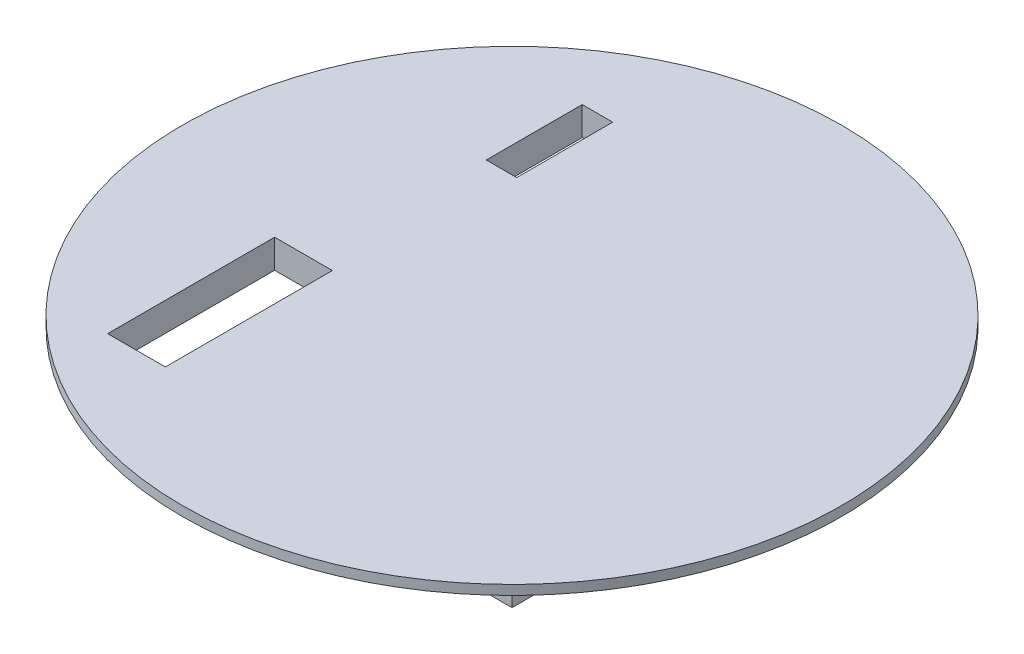
SolidWorks part; units mm, degrees
ref_plane "Front Plane" through (0, 0, 0) normal (0, 0, 1) x (1, 0, 0)
ref_plane "Top Plane" through (0, 0, 0) normal (0, 1, 0) x (1, 0, 0)
ref_plane "Right Plane" through (0, 0, 0) normal (1, 0, 0) x (0, 0, -1)
sketch "Sketch1" plane through (0, 0, 0) normal (0, 1, 0) x (1, 0, 0)
  line L5 (-23.5, -23.5) -> (23.5, -23.5)
  line L6 (-23.5, -23.5) -> (-23.5, 23.5)
  line L7 (-23.5, 23.5) -> (23.5, 23.5)
  line L8 (23.5, -23.5) -> (23.5, 23.5)
  line L9 (-23.5, -23.5) -> (23.5, 23.5) construction
  line L10 (-23.5, 23.5) -> (23.5, -23.5) construction
  line L11 (-19.5113, -22.8198) -> (-13.4704, -22.8198)
  line L12 (-19.5113, -22.8198) -> (-19.5113, -5.3378)
  line L13 (-19.5113, -5.3378) -> (-13.4704, -5.3378)
  line L14 (-13.4704, -22.8198) -> (-13.4704, -5.3378)
  line L15 (-15.4354, 22.788) -> (-12.2457, 22.788)
  line L16 (-15.4354, 22.788) -> (-15.4354, 12.7402)
  line L17 (-15.4354, 12.7402) -> (-12.2457, 12.7402)
  line L18 (-12.2457, 22.788) -> (-12.2457, 12.7402)
  dimension "D1" = 3.9887
  dimension "D2" = 0.6802
extrude "Boss-Extrude2" add sketch "Sketch1" along normal blind 2
sketch "Sketch6" plane through (0, 2, 0) normal (0, 1, 0) x (1, 0, 0)
  line L1 (-15.4354, 22.788) -> (-12.2457, 22.788)
  line L2 (-15.4354, 22.788) -> (-15.4354, 12.7402)
  line L3 (-15.4354, 12.7402) -> (-12.2457, 12.7402)
  line L4 (-12.2457, 22.788) -> (-12.2457, 12.7402)
  line L5 (-19.5113, -5.3378) -> (-13.4704, -5.3378)
  line L6 (-19.5113, -5.3378) -> (-19.5113, -22.8198)
  line L7 (-19.5113, -22.8198) -> (-13.4704, -22.8198)
  line L8 (-13.4704, -5.3378) -> (-13.4704, -22.8198)
  circle A0 centre (0, 0) radius 34.5
extrude "Boss-Extrude4" add sketch "Sketch6" along normal blind 1
